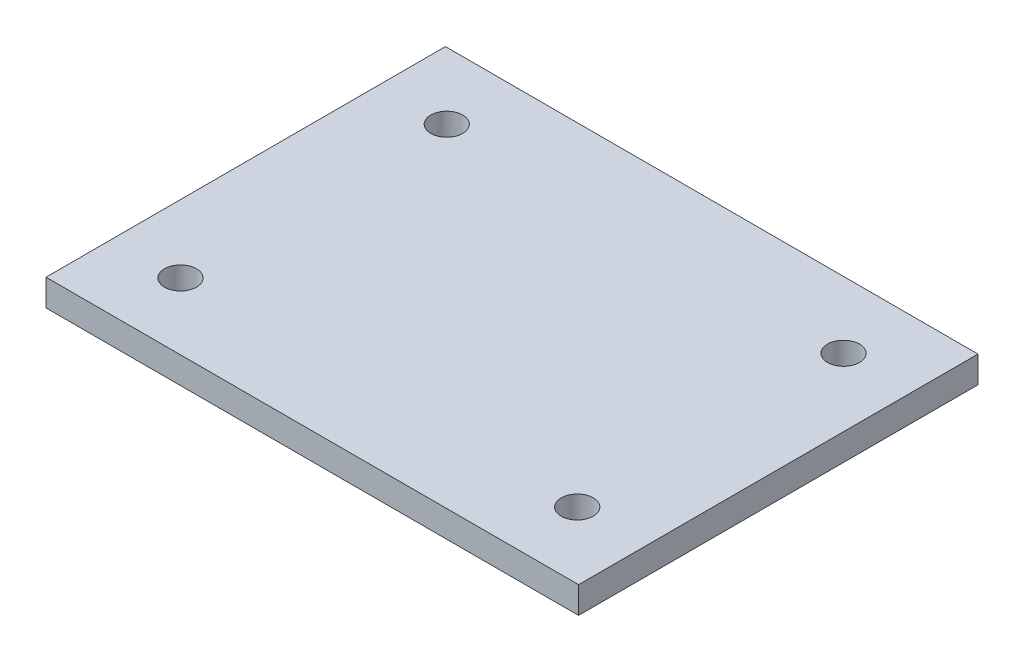
SolidWorks part; units mm, degrees
material "AISI 1020"
ref_plane "Front Plane" through (0, 0, 0) normal (0, 0, 1) x (1, 0, 0)
ref_plane "Top Plane" through (0, 0, 0) normal (0, 1, 0) x (1, 0, 0)
ref_plane "Right Plane" through (0, 0, 0) normal (1, 0, 0) x (0, 0, -1)
sketch "Sketch1" plane through (0, 0, 0) normal (0, 1, 0) x (1, 0, 0)
  line L1 (-100, -75) -> (100, -75)
  line L2 (-100, -75) -> (-100, 75)
  line L3 (-100, 75) -> (100, 75)
  line L4 (100, -75) -> (100, 75)
  line L5 (-100, -75) -> (100, 75) construction
  line L6 (-100, 75) -> (100, -75) construction
  point P0 (0, 0)
  dimension "D1" = 200
  dimension "D2" = 150
extrude "Boss-Extrude1" add sketch "Sketch1" along normal blind 10
sketch "Sketch2" plane through (0, 10, 0) normal (0, 1, 0) x (1, 0, 0)
  line L1 (-74.5, -50) -> (74.5, -50) construction
  line L2 (-74.5, -50) -> (-74.5, 50) construction
  line L3 (-74.5, 50) -> (74.5, 50) construction
  line L4 (74.5, -50) -> (74.5, 50) construction
  line L5 (-74.5, -50) -> (74.5, 50) construction
  line L6 (-74.5, 50) -> (74.5, -50) construction
  circle A0 centre (74.5, 50) radius 6
  circle A1 centre (74.5, -50) radius 6
  circle A2 centre (-74.5, -50) radius 6
  circle A3 centre (-74.5, 50) radius 6
  point P0 (0, 0)
  dimension "D1" = 12
  dimension "D2" = 149
  dimension "D3" = 100
extrude "Cut-Extrude1" cut sketch "Sketch2" against normal up to next
